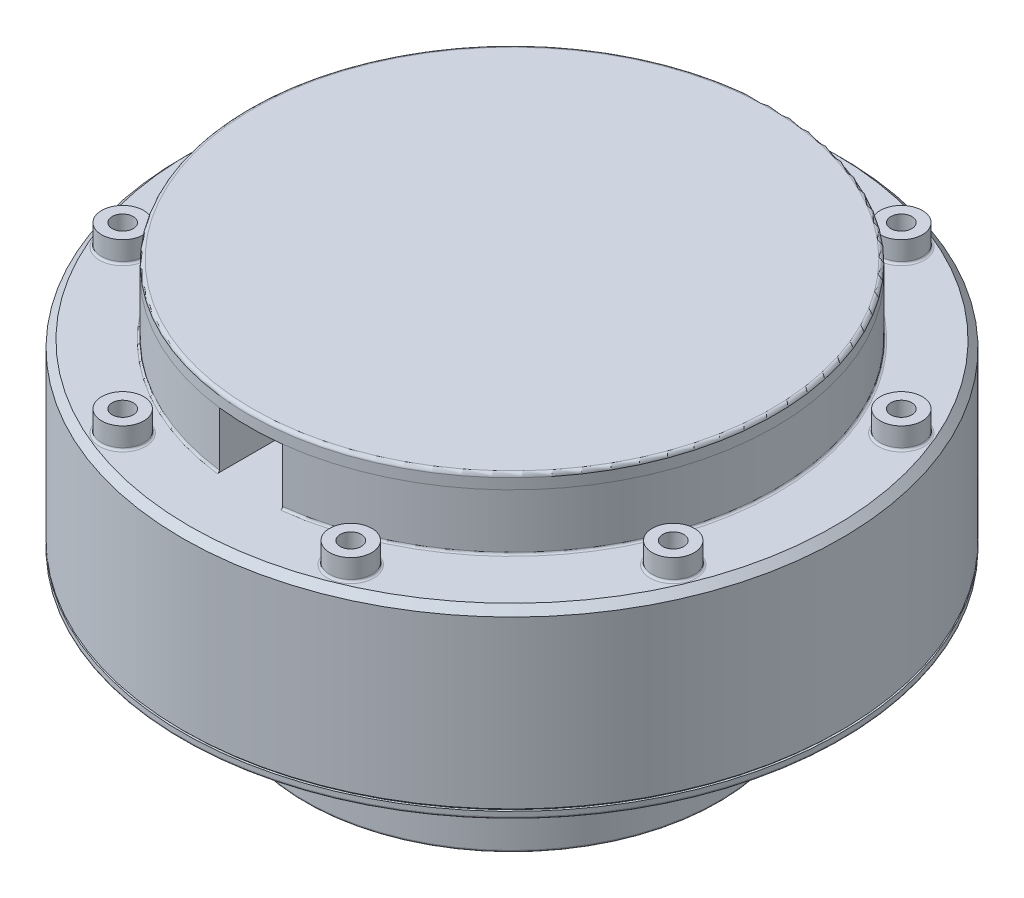
SolidWorks part; units mm, degrees
material "6061 合金"
ref_plane "前视基准面" through (0, 0, 0) normal (0, 0, 1) x (1, 0, 0)
ref_plane "上视基准面" through (0, 0, 0) normal (0, 1, 0) x (1, 0, 0)
ref_plane "右视基准面" through (0, 0, 0) normal (1, 0, 0) x (0, 0, -1)
sketch "草图1" plane through (0, 0, 0) normal (0, 1, 0) x (1, 0, 0)
  line L1 (16.264, -39.2649) -> (39.2649, -16.264) construction
  line L2 (39.2649, -16.264) -> (39.2649, 16.264) construction
  line L3 (39.2649, 16.264) -> (16.264, 39.2649) construction
  line L4 (16.264, 39.2649) -> (-16.264, 39.2649) construction
  line L5 (-16.264, 39.2649) -> (-39.2649, 16.264) construction
  line L6 (-39.2649, 16.264) -> (-39.2649, -16.264) construction
  line L7 (-39.2649, -16.264) -> (-16.264, -39.2649) construction
  line L8 (-16.264, -39.2649) -> (16.264, -39.2649) construction
  circle A0 centre (0, 0) radius 42.5 construction
  circle A1 centre (0, 0) radius 47
  circle A2 centre (0, 0) radius 39.2649 construction
  circle A3 centre (-16.264, 39.2649) radius 1.5
  circle A4 centre (16.264, 39.2649) radius 1.5
  circle A5 centre (39.2649, 16.264) radius 1.5
  circle A6 centre (39.2649, -16.264) radius 1.5
  circle A7 centre (16.264, -39.2649) radius 1.5
  circle A8 centre (-16.264, -39.2649) radius 1.5
  circle A9 centre (-39.2649, -16.264) radius 1.5
  circle A10 centre (-39.2649, 16.264) radius 1.5
  dimension "D1" = 85
  dimension "D2" = 94
  dimension "D3" = 3
extrude "凸台-拉伸1" add sketch "草图1" along normal blind 25
sketch "草图2" plane through (0, 25, 0) normal (0, 1, 0) x (1, 0, 0)
  circle A0 centre (-16.264, 39.2649) radius 3
  circle A1 centre (16.264, 39.2649) radius 1.5
  circle A2 centre (16.264, 39.2649) radius 1.5
  circle A3 centre (-16.264, 39.2649) radius 1.5
  circle A4 centre (-16.264, 39.2649) radius 1.5
  circle A5 centre (39.2649, 16.264) radius 1.5
  circle A6 centre (39.2649, 16.264) radius 1.5
  circle A7 centre (39.2649, -16.264) radius 1.5
  circle A8 centre (39.2649, -16.264) radius 1.5
  circle A9 centre (16.264, -39.2649) radius 1.5
  circle A10 centre (16.264, -39.2649) radius 1.5
  circle A11 centre (-16.264, -39.2649) radius 1.5
  circle A12 centre (-16.264, -39.2649) radius 1.5
  circle A13 centre (-39.2649, -16.264) radius 1.5
  circle A14 centre (-39.2649, -16.264) radius 1.5
  circle A15 centre (-39.2649, 16.264) radius 1.5
  circle A16 centre (-39.2649, 16.264) radius 1.5
  circle A17 centre (16.264, 39.2649) radius 3
  circle A18 centre (39.2649, 16.264) radius 3
  circle A19 centre (39.2649, -16.264) radius 3
  circle A20 centre (16.264, -39.2649) radius 3
  circle A21 centre (-16.264, -39.2649) radius 3
  circle A22 centre (-39.2649, -16.264) radius 3
  circle A23 centre (-39.2649, 16.264) radius 3
  dimension "D9" = 6
  dimension "D1" = 0
  dimension "D2" = 0
  dimension "D3" = 0
  dimension "D4" = 0
  dimension "D5" = 0
  dimension "D6" = 0
  dimension "D7" = 0
  dimension "D8" = 0
extrude "凸台-拉伸2" add sketch "草图2" along normal blind 3
sketch "草图3" plane through (0, 25, 0) normal (0, 1, 0) x (1, 0, 0)
  line L1 (-4.5, 0) -> (4.5, 0)
  line L2 (-4.5, 0) -> (-4.5, -47)
  line L3 (-4.5, -47) -> (4.5, -47)
  line L4 (4.5, 0) -> (4.5, -47)
  line L5 (-4.5, 0) -> (4.5, -47) construction
  line L6 (-4.5, -47) -> (4.5, 0) construction
  circle A0 centre (0, 0) radius 37.5
  circle A1 centre (0, 0) radius 47 construction
  point P3 (0, -23.5)
  dimension "D1" = 75
  dimension "D2" = 9
extrude "凸台-拉伸3" add sketch "草图3" along normal blind 8 contours L4 A0 L2 L1
sketch "草图4" plane through (0, 33, 0) normal (0, 1, 0) x (1, 0, 0)
  circle A0 centre (0, 0) radius 37.505
  dimension "D1" = 75.01
extrude "凸台-拉伸4" add sketch "草图4" along normal blind 2
fillet "圆角1" radius 0.5 1 edges at (0, 35, 37.505)
chamfer "倒角1" distance 1 angle 45 1 edges at (0, 25, 47)
fillet "圆角2" radius 0.3 9 edges at (0, 25, -37.5) (16.264, 25, 42.2649) (39.2649, 25, 19.264) (39.2649, 25, -13.264) (16.264, 25, -36.2649) (-16.264, 25, -36.2649) (-39.2649, 25, -13.264) (-39.2649, 25, 19.264) (-16.264, 25, 42.2649)
chamfer "倒角2" distance 0.3 angle 45 1 edges at (0, 0, 47)
sketch "草图5" plane through (0, 0, 0) normal (0, -1, 0) x (1, 0, 0)
  circle A1 centre (0, 0) radius 47
  circle A2 centre (16.264, -39.2649) radius 1.5
  circle A3 centre (16.264, -39.2649) radius 1.5
  circle A4 centre (-16.264, -39.2649) radius 1.5
  circle A5 centre (-16.264, -39.2649) radius 1.5
  circle A6 centre (39.2649, -16.264) radius 1.5
  circle A7 centre (39.2649, -16.264) radius 1.5
  circle A8 centre (39.2649, 16.264) radius 1.5
  circle A9 centre (39.2649, 16.264) radius 1.5
  circle A10 centre (16.264, 39.2649) radius 1.5
  circle A11 centre (16.264, 39.2649) radius 1.5
  circle A12 centre (-16.264, 39.2649) radius 1.5
  circle A13 centre (-16.264, 39.2649) radius 1.5
  circle A14 centre (-39.2649, 16.264) radius 1.5
  circle A15 centre (-39.2649, 16.264) radius 1.5
  circle A16 centre (-39.2649, -16.264) radius 1.5
  circle A17 centre (-39.2649, -16.264) radius 1.5
  circle A19 centre (0, 0) radius 47 construction
  dimension "D1" = 0
  dimension "D2" = 0
  dimension "D3" = 0
  dimension "D4" = 0
  dimension "D5" = 0
  dimension "D6" = 0
  dimension "D7" = 0
  dimension "D8" = 0
extrude "凸台-拉伸5" add sketch "草图5" along normal blind 1
fillet "圆角3" radius 0.3 1 edges at (0, -1, -47)
sketch "草图6" plane through (0, -1, 0) normal (0, -1, 0) x (1, 0, 0)
  circle A0 centre (0, 0) radius 29.5
  circle A1 centre (0, 0) radius 27.5
  dimension "D1" = 59
  dimension "D2" = 55
extrude "凸台-拉伸6" add sketch "草图6" along normal blind 16.5
sketch "草图7" plane through (0, -1, 0) normal (0, -1, 0) x (1, 0, 0)
  circle A0 centre (0, 0) radius 22
  circle A1 centre (0, 0) radius 27.5
  circle A2 centre (0, 0) radius 27.5 construction
  dimension "D1" = 44
extrude "凸台-拉伸7" add sketch "草图7" along normal offset from surface (7.5 mm away) 9 up to face at (0, -17.5, -29.5)
sketch "草图8" plane through (0, -1, 0) normal (0, -1, 0) x (1, 0, 0)
  circle A0 centre (0, 0) radius 21
  dimension "D1" = 42
extrude "凸台-拉伸8" add sketch "草图8" along normal offset from surface (7 mm away) 9.5 up to face at (0, -17.5, -29.5)
sketch "草图9" plane through (0, -8, 0) normal (0, -1, 0) x (1, 0, 0)
  circle A0 centre (0, 0) radius 20
  dimension "D1" = 40
extrude "凸台-拉伸9" add sketch "草图9" along normal blind 10
sketch "草图10" plane through (0, -18, 0) normal (0, -1, 0) x (1, 0, 0)
  circle A0 centre (0, 0) radius 9.75
  dimension "D1" = 19.5
extrude "切除-拉伸1" cut sketch "草图10" against normal blind 5.5
sketch "草图11" plane through (0, -18, 0) normal (0, -1, 0) x (1, 0, 0)
  line L0 (0, 12.9615) -> (0, 15.9687)
  line L1 (7.2321, 10.7562) -> (8.9101, 13.2518)
  line L2 (5.6991, -11.6413) -> (7.0214, -14.3423)
  line L3 (11.225, -6.4807) -> (13.8293, -7.9844)
  line L4 (-12.9312, 0.8851) -> (-15.9314, 1.0904)
  line L5 (-11.225, -6.4807) -> (-13.8293, -7.9844)
  circle A0 centre (0, 0) radius 12 construction
  circle A1 centre (0, 0) radius 17 construction
  arc A2 (0.9231, 11.9644) -> (5.9098, 10.4439) centre (0, 0) cw
  arc A3 (1.0625, 16.9668) -> (8.5852, 14.6729) centre (0, 0) cw
  arc A4 (8.9101, 13.2518) -> (8.5852, 14.6729) centre (8.0802, 13.8098) ccw
  arc A5 (5.9098, 10.4439) -> (7.2321, 10.7562) centre (6.4023, 11.3142) ccw
  arc A6 (0.9231, 11.9644) -> (0, 12.9615) centre (1, 12.9615) cw
  arc A7 (0, 15.9687) -> (1.0625, 16.9668) centre (1, 15.9687) cw
  arc A8 (14.1624, -9.4035) -> (8.4145, -14.7715) centre (0, 0) cw
  arc A9 (13.8293, -7.9844) -> (14.1624, -9.4035) centre (13.3293, -8.8504) cw
  arc A10 (7.0214, -14.3423) -> (8.4145, -14.7715) centre (7.9195, -13.9026) ccw
  arc A11 (6.0898, -10.34) -> (5.6991, -11.6413) centre (6.5973, -11.2016) ccw
  arc A12 (9.9, -6.7816) -> (6.0898, -10.34) centre (0, 0) cw
  arc A13 (9.9, -6.7816) -> (11.225, -6.4807) centre (10.725, -7.3468) cw
  arc A14 (-15.2249, -7.5632) -> (-16.9997, 0.0986) centre (0, 0) cw
  arc A15 (-13.8293, -7.9844) -> (-15.2249, -7.5632) centre (-14.3293, -7.1183) cw
  arc A16 (-15.9314, 1.0904) -> (-16.9997, 0.0986) centre (-15.9997, 0.0928) ccw
  arc A17 (-11.9995, -0.1039) -> (-12.9312, 0.8851) centre (-12.9995, -0.1126) ccw
  arc A18 (-10.8231, -5.1828) -> (-11.9995, -0.1039) centre (0, 0) cw
  arc A19 (-10.8231, -5.1828) -> (-11.225, -6.4807) centre (-11.725, -5.6147) cw
  point P12 (9.4855, 14.1076)
  point P15 (6.6956, 9.9583)
  point P18 (0, 12)
  point P21 (0, 17)
  point P48 (0, 0)
  dimension "D1" = 24
  dimension "D2" = 34
  dimension "D4" = 1
  dimension "D3" = 7
  dimension "D5" = 3
extrude "切除-拉伸2" cut sketch "草图11" against normal blind 5.6
sketch "草图12" plane through (0, -18, 0) normal (0, -1, 0) x (1, 0, 0)
  line L0 (1.0625, 16.9668) -> (8.5852, 14.6729) construction
  line L1 (-3.0618, 13.2177) -> (-12.9778, 3.9573) construction
  line L2 (-12.9778, 3.9573) -> (-9.916, -9.2605) construction
  line L3 (-9.916, -9.2605) -> (3.0618, -13.2177) construction
  line L4 (3.0618, -13.2177) -> (12.9778, -3.9573) construction
  line L5 (12.9778, -3.9573) -> (9.916, 9.2605) construction
  line L6 (9.916, 9.2605) -> (-3.0618, 13.2177) construction
  circle A0 centre (0, 0) radius 11.75 construction
  circle A1 centre (-3.0618, 13.2177) radius 1.5
  circle A2 centre (9.916, 9.2605) radius 1.5
  circle A3 centre (12.9778, -3.9573) radius 1.5
  circle A4 centre (3.0618, -13.2177) radius 1.5
  circle A5 centre (-9.916, -9.2605) radius 1.5
  circle A6 centre (-12.9778, 3.9573) radius 1.5
  dimension "D2" = 3
  dimension "D1" = 23.5
extrude "切除-拉伸3" cut sketch "草图12" against normal blind 6
sketch "草图13" plane through (0, -18, 0) normal (0, -1, 0) x (1, 0, 0)
  line L0 (-3.0618, 13.2177) -> (-2.708, 11.6904) construction
  line L1 (-4.0415, -13.2539) -> (9.4575, -10.127) construction
  line L2 (9.4575, -10.127) -> (13.499, 3.127) construction
  line L3 (13.499, 3.127) -> (4.0415, 13.2539) construction
  line L4 (4.0415, 13.2539) -> (-9.4575, 10.127) construction
  line L5 (-9.4575, 10.127) -> (-13.499, -3.127) construction
  line L6 (-13.499, -3.127) -> (-4.0415, -13.2539) construction
  circle A0 centre (0, 0) radius 12 construction
  circle A1 centre (-9.4575, 10.127) radius 2
  circle A2 centre (13.499, 3.127) radius 2
  circle A3 centre (-4.0415, -13.2539) radius 2
  dimension "D2" = 4
  dimension "D1" = 24
extrude "凸台-拉伸10" add sketch "草图13" along normal blind 2.6
chamfer "倒角3" distance 0.5 angle 45 1 edges at (0, -18, -20)
chamfer "倒角4" distance 0.2 angle 45 31 edges at (0, -18, -9.75) (6.3602, -18, -12.9918) (7.6251, -18, -14.8582) (5.6395, -18, -10.9141) (11.6031, -18, -12.4245) (8.1904, -18, -8.7702) (14.3029, -18, -8.6219) (10.5035, -18, -6.3716) (12.5271, -18, -7.2326) (0.3153, -18, 16.6976) (0, -18, 14.4651) (4.9583, -18, 16.2608) (0.2662, -18, 12.2821) (9.0551, -18, 14.0326) (3.5, -18, 11.4782) (8.0711, -18, 12.004) (6.6321, -18, 10.341) (-16.5615, -18, -3.8364) (-14.6182, -18, -8.0757) (-16.6801, -18, 0.8256) (-12.5271, -18, -7.2326) (-14.4313, -18, 0.9878) (-10.7697, -18, -5.9105) (-12.2716, -18, 0.5731) (-11.6904, -18, -2.708) (-12.9778, -18, 2.4573) (-9.916, -18, -10.7605) (12.9778, -18, -5.4573) (9.916, -18, 7.7605) (-3.0618, -18, 11.7177) (3.0618, -18, -14.7177)
fillet "圆角4" radius 0.3 5 edges at (0, -8.5, -27.5) (0, -17.5, -27.5) (0, -17.5, -29.5) (0, -1, -29.5) (0, -8, -20)
sketch "草图15" plane through (0, -1, 0) normal (0, -1, 0) x (1, 0, 0)
  circle A0 centre (0, 0) radius 19.25
  dimension "D1" = 38.5
extrude "切除-拉伸4" cut sketch "草图15" against normal up to surface (26 mm away) and the other way blind 6 up to face at (16.264, 25, 42.5649)
